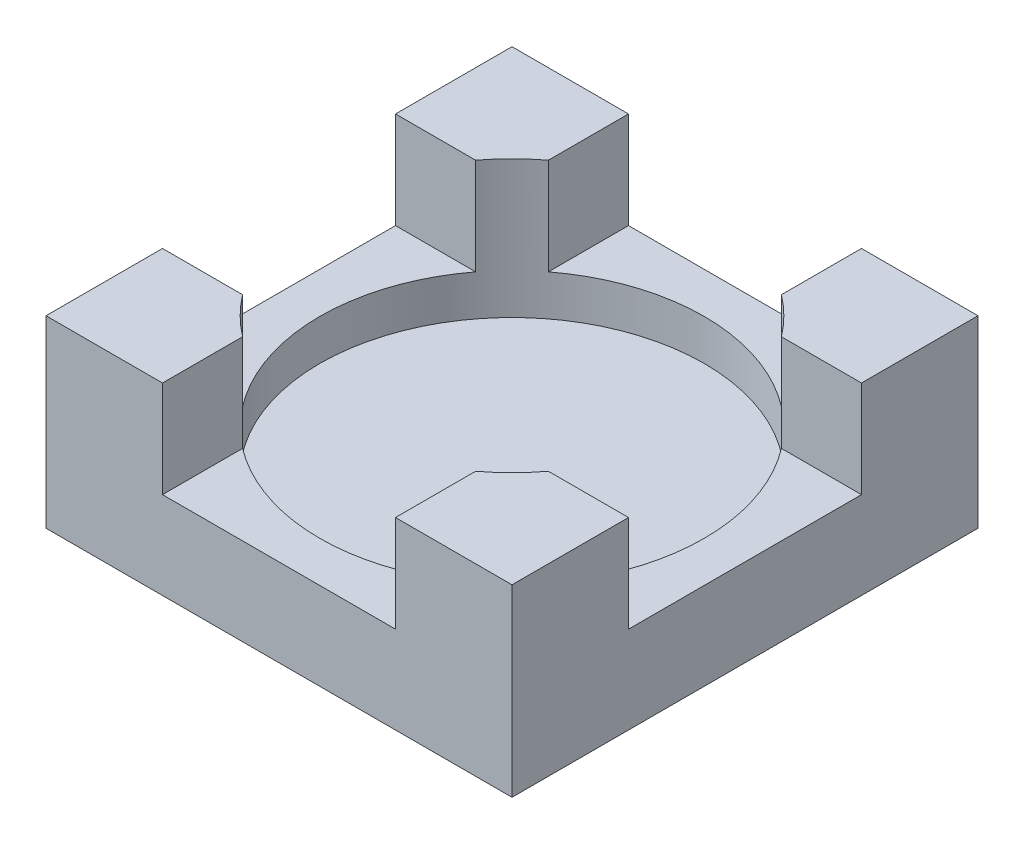
SolidWorks part; units mm, degrees
ref_plane "Front Plane" through (0, 0, 0) normal (0, 0, 1) x (1, 0, 0)
ref_plane "Top Plane" through (0, 0, 0) normal (0, 1, 0) x (1, 0, 0)
ref_plane "Right Plane" through (0, 0, 0) normal (1, 0, 0) x (0, 0, -1)
sketch "Sketch1" plane through (0, 0, 0) normal (0, 1, 0) x (1, 0, 0)
  line L1 (-20, -20) -> (20, -20)
  line L2 (-20, -20) -> (-20, 20)
  line L3 (-20, 20) -> (20, 20)
  line L4 (20, -20) -> (20, 20)
  line L5 (-20, -20) -> (20, 20) construction
  line L6 (-20, 20) -> (20, -20) construction
  point P0 (0, 0)
extrude "Boss-Extrude1" add sketch "Sketch1" along normal blind 90
sketch "Sketch2" plane through (0, 90, 0) normal (0, 1, 0) x (1, 0, 0)
  circle A0 centre (0, 0) radius 18.5
extrude "Cut-Extrude1" cut sketch "Sketch2" against normal blind 45
sketch "Sketch3" plane through (0, 45, 0) normal (0, 1, 0) x (1, 0, 0)
  circle A0 centre (0, 0) radius 16.5
extrude "Cut-Extrude2" cut sketch "Sketch3" against normal blind 41
sketch "Sketch4" plane through (0, 90, 0) normal (0, 1, 0) x (1, 0, 0)
  line L1 (-20, -20) -> (20, -20)
  line L2 (-20, -20) -> (-20, 20)
  line L3 (-20, 20) -> (20, 20)
  line L4 (20, -20) -> (20, 20)
  line L5 (-20, -20) -> (20, 20) construction
  line L6 (-20, 20) -> (20, -20) construction
  point P0 (0, 0)
extrude "Cut-Extrude3" cut sketch "Sketch4" against normal blind 21
sketch "Sketch6" plane through (0, 0, 20) normal (0, 0, 1) x (1, 0, 0)
  line L0 (0, 0) -> (0, 15) construction
  line L2 (-10, 7.5) -> (10, 7.5)
  line L3 (-10, 7.5) -> (-10, 22.5)
  line L4 (-10, 22.5) -> (10, 22.5)
  line L5 (10, 7.5) -> (10, 22.5)
  line L6 (-10, 7.5) -> (10, 22.5) construction
  line L7 (-10, 22.5) -> (10, 7.5) construction
extrude "Cut-Extrude4" cut sketch "Sketch6" against normal through all contours L3 L2 L5 L4
sketch "Sketch8" plane through (-20, 0, 0) normal (-1, 0, 0) x (0, 0, 1)
  line L0 (0, 0) -> (0, 15) construction
  line L2 (-10, 7.5) -> (10, 7.5)
  line L3 (-10, 7.5) -> (-10, 22.5)
  line L4 (-10, 22.5) -> (10, 22.5)
  line L5 (10, 7.5) -> (10, 22.5)
  line L6 (-10, 7.5) -> (10, 22.5) construction
  line L7 (-10, 22.5) -> (10, 7.5) construction
extrude "Cut-Extrude5" cut sketch "Sketch8" against normal through all contours L3 L2 L5 L4
sketch "Sketch11" plane through (0, 0, 20) normal (0, 0, 1) x (1, 0, 0)
  line L0 (0, 0) -> (0, 28.5) construction
  line L1 (-20, 0) -> (20, 0) construction
  line L2 (-20, 28.5) -> (20, 28.5) construction
  line L3 (20, 69) -> (20, 0) construction
  line L4 (-20, 28.5) -> (-20, 15.8) construction
  line L5 (-20, 69) -> (-20, 0) construction
  line L7 (-20, 15.8) -> (20, 15.8)
  line L8 (-20, 15.8) -> (-20, 69)
  line L9 (-20, 69) -> (20, 69)
  line L10 (20, 15.8) -> (20, 69)
  point P9 (0, 28.5)
extrude "Cut-Extrude7" cut sketch "Sketch11" against normal through all
